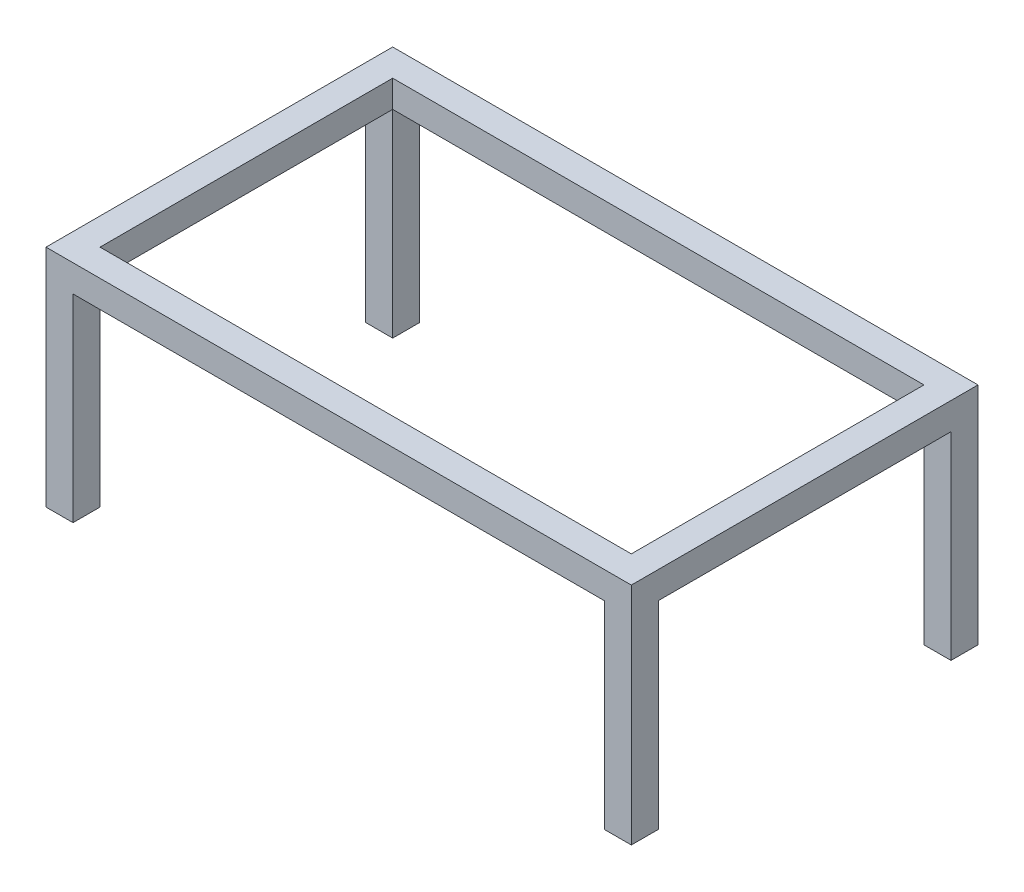
SolidWorks part; units mm, degrees
ref_plane "Plan de face" through (0, 0, 0) normal (0, 0, 1) x (1, 0, 0)
ref_plane "Plan de dessus" through (0, 0, 0) normal (0, 1, 0) x (1, 0, 0)
ref_plane "Plan de droite" through (0, 0, 0) normal (1, 0, 0) x (0, 0, -1)
sketch "Esquisse2" plane through (0, 0, 0) normal (0, 1, 0) x (1, 0, 0)
  line L1 (0, 0) -> (13000, 0)
  line L2 (0, 0) -> (0, 7700)
  line L3 (0, 7700) -> (13000, 7700)
  line L4 (13000, 0) -> (13000, 7700)
  point P9 (14500, 647.2807)
  point P10 (0, 0)
  point P11 (0, 0)
  dimension "D1" = 13000
  dimension "D2" = 7700
extrude "Boss.-Extru.1" add sketch "Esquisse2" against normal blind 5000
sketch "Esquisse6" plane through (0, 0, 0) normal (0, 1, 0) x (1, 0, 0)
  line L0 (0, 7700) -> (0, 0) construction
  line L1 (600, 7100) -> (12400, 7100)
  line L2 (600, 7100) -> (600, 600)
  line L3 (600, 600) -> (12400, 600)
  line L4 (12400, 7100) -> (12400, 600)
  line L5 (13000, 7700) -> (0, 7700) construction
  line L6 (0, 0) -> (13000, 0) construction
  line L7 (13000, 0) -> (13000, 7700) construction
  dimension "D1" = 600
  dimension "D2" = 600
  dimension "D3" = 600
  dimension "D4" = 600
extrude "Enlèv. mat.-Extru.2" cut sketch "Esquisse6" against normal blind 5000
sketch "Esquisse7" plane through (0, 0, 0) normal (0, 0, 1) x (1, 0, 0)
  line L0 (0, -5000) -> (13000, -5000) construction
  line L1 (600, -600) -> (12400, -600)
  line L2 (600, -600) -> (600, -5000)
  line L3 (600, -5000) -> (12400, -5000)
  line L4 (12400, -600) -> (12400, -5000)
  line L5 (0, 0) -> (13000, 0) construction
  line L6 (0, -5000) -> (0, 0) construction
  line L7 (13000, -5000) -> (13000, 0) construction
  dimension "D1" = 600
  dimension "D2" = 600
  dimension "D3" = 600
extrude "Enlèv. mat.-Extru.3" cut sketch "Esquisse7" against normal through all
sketch "Esquisse10" plane through (0, 0, 0) normal (-1, 0, 0) x (0, 0, 1)
  line L0 (-7700, -5000) -> (0, -5000) construction
  line L1 (-7100, -600) -> (-600, -600)
  line L2 (-7100, -600) -> (-7100, -5000)
  line L3 (-7100, -5000) -> (-600, -5000)
  line L4 (-600, -600) -> (-600, -5000)
  line L5 (-7700, 0) -> (0, 0) construction
  line L6 (-7700, -5000) -> (-7700, 0) construction
  line L7 (0, -5000) -> (0, 0) construction
  dimension "D1" = 600
  dimension "D2" = 600
  dimension "D3" = 600
extrude "Enlèv. mat.-Extru.4" cut sketch "Esquisse10" against normal through all
